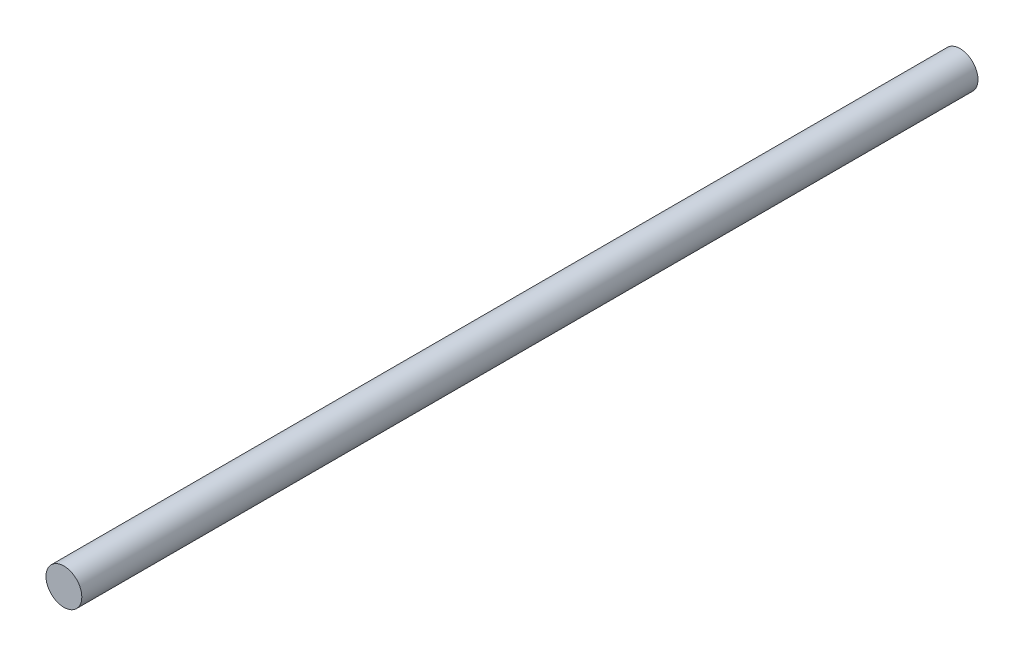
SolidWorks part; units mm, degrees
ref_plane "Front Plane" through (0, 0, 0) normal (0, 0, 1) x (1, 0, 0)
ref_plane "Top Plane" through (0, 0, 0) normal (0, 1, 0) x (1, 0, 0)
ref_plane "Right Plane" through (0, 0, 0) normal (1, 0, 0) x (0, 0, -1)
sketch "Sketch1" plane through (0, 0, 0) normal (0, 0, 1) x (1, 0, 0)
  circle A0 centre (0, 0) radius 0.508
  dimension "D1" = 1.016
extrude "Boss-Extrude1" add sketch "Sketch1" along normal blind 25.4
